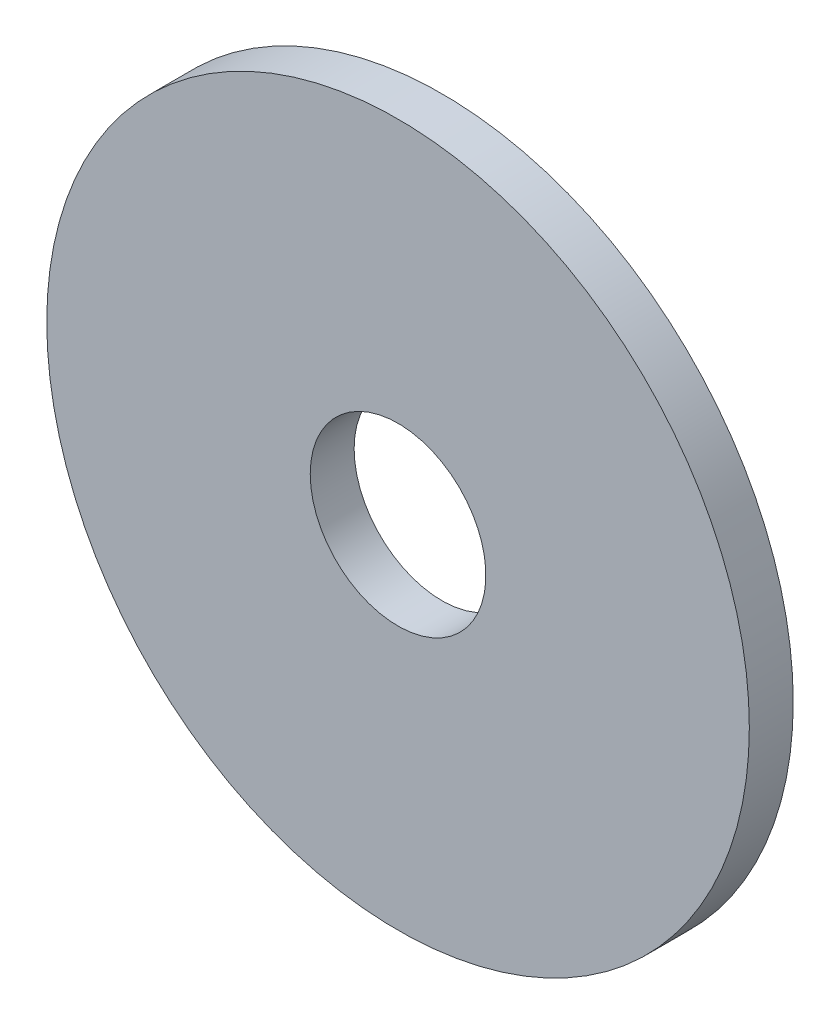
SolidWorks part; units mm, degrees
ref_plane "Front Plane" through (0, 0, 0) normal (0, 0, 1) x (1, 0, 0)
ref_plane "Top Plane" through (0, 0, 0) normal (0, 1, 0) x (1, 0, 0)
ref_plane "Right Plane" through (0, 0, 0) normal (1, 0, 0) x (0, 0, -1)
sketch "Sketch1" plane through (0, 0, 0) normal (0, 0, 1) x (1, 0, 0)
  circle A0 centre (68.3982, 3.2144) radius 6.35
  dimension "D1" = 12.7
extrude "Boss-Extrude1" add sketch "Sketch1" along normal blind 0.7937
sketch "Sketch2" plane through (0, 0, 0) normal (0, 0, -1) x (-1, 0, 0)
  circle A0 centre (-68.3982, 3.2144) radius 1.5875
  dimension "D1" = 3.175
extrude "Cut-Extrude1" cut sketch "Sketch2" against normal blind 0.7937
